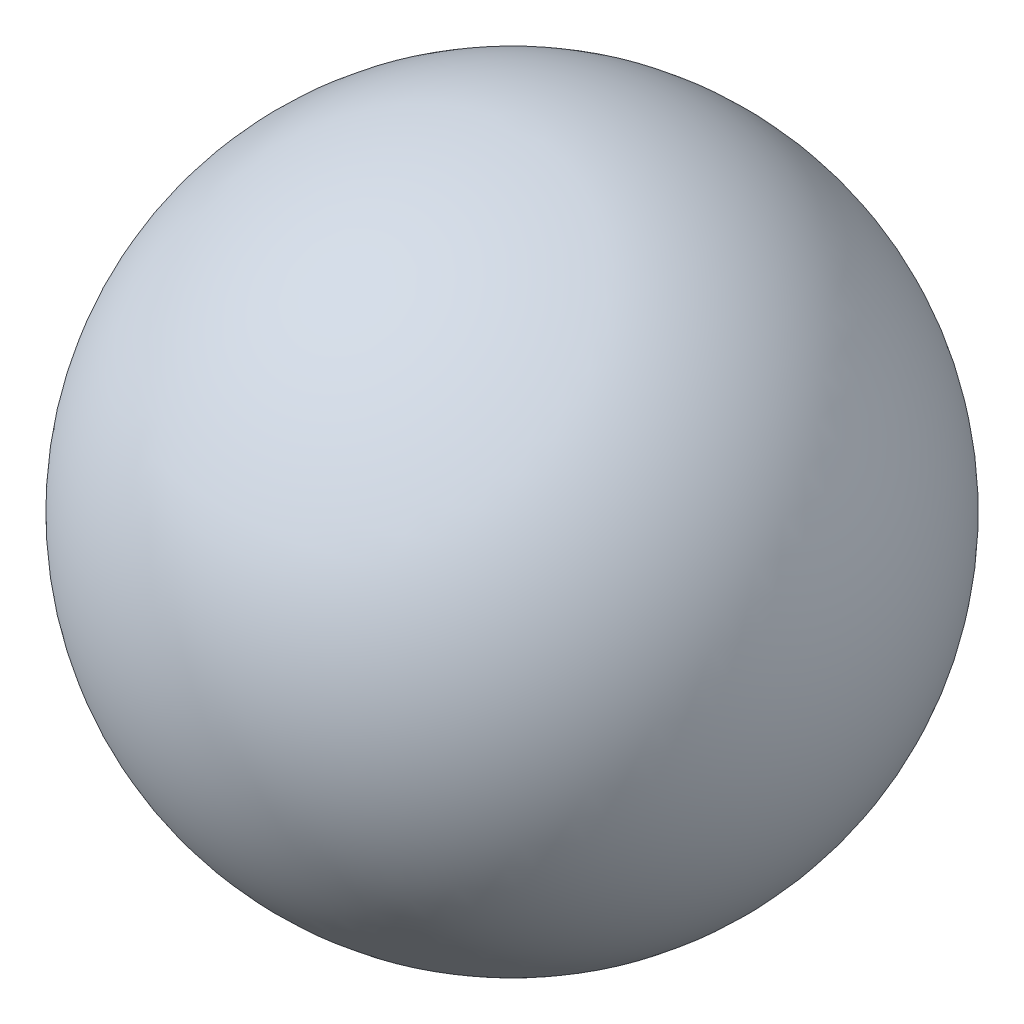
SolidWorks part; units mm, degrees
ref_plane "Front Plane" through (0, 0, 0) normal (0, 0, 1) x (1, 0, 0)
ref_plane "Top Plane" through (0, 0, 0) normal (0, 1, 0) x (1, 0, 0)
ref_plane "Right Plane" through (0, 0, 0) normal (1, 0, 0) x (0, 0, -1)
sketch "Sketch2" plane through (0, 0, 0) normal (0, 0, 1) x (1, 0, 0)
  line L0 (0, 254) -> (0, -254)
  arc A0 (0, 254) -> (0, -254) centre (0, 0) ccw
  point P4 (0, 0)
revolve "Revolve1" add sketch "Sketch2" angle 360 about L0
